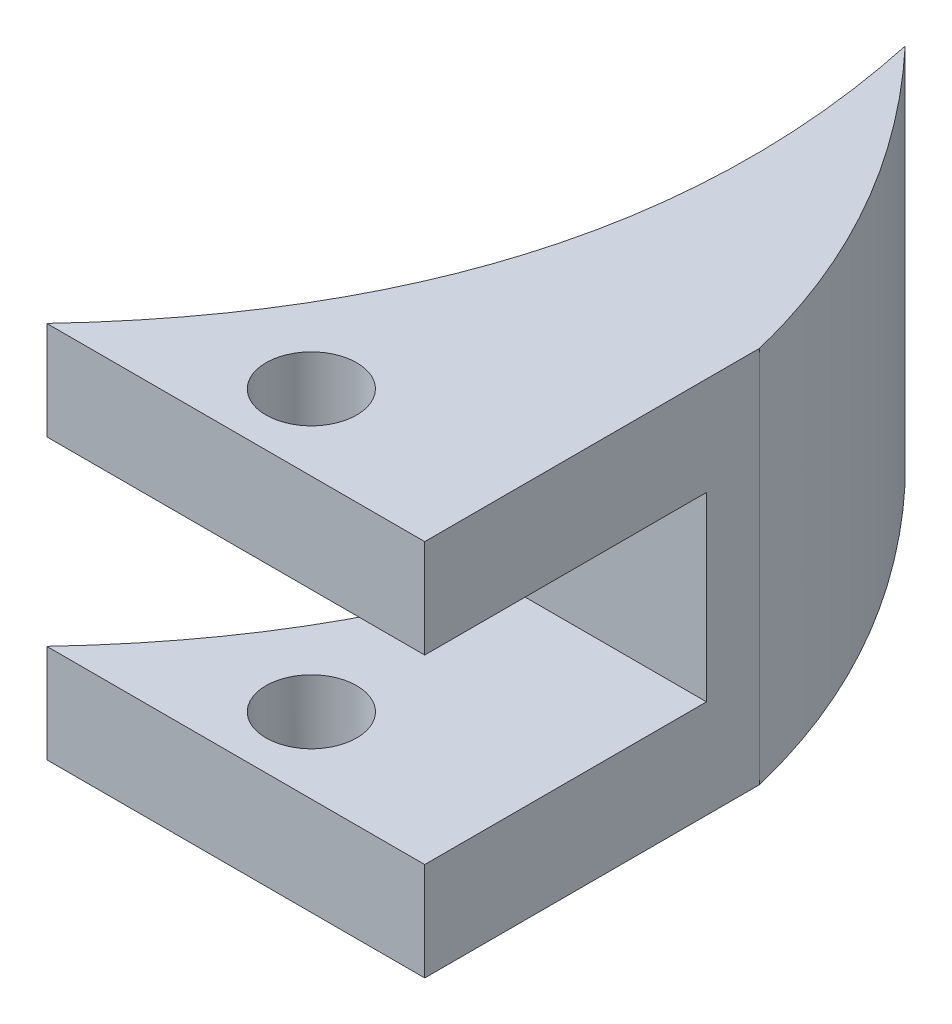
SolidWorks part; units mm, degrees
ref_plane "정면" through (0, 0, 0) normal (0, 0, 1) x (1, 0, 0)
ref_plane "윗면" through (0, 0, 0) normal (0, 1, 0) x (1, 0, 0)
ref_plane "우측면" through (0, 0, 0) normal (1, 0, 0) x (0, 0, -1)
sketch "스케치1" plane through (0, 0, 0) normal (0, 0, 1) x (1, 0, 0)
  line L1 (-12.5, -12.5) -> (12.5, -12.5)
  line L2 (-12.5, -12.5) -> (-12.5, 12.5)
  line L3 (-12.5, 12.5) -> (12.5, 12.5)
  line L4 (12.5, -12.5) -> (12.5, 12.5)
  line L5 (-12.5, -12.5) -> (12.5, 12.5) construction
  line L6 (-12.5, 12.5) -> (12.5, -12.5) construction
  point P0 (0, 0)
  dimension "D1" = 25
extrude "보스-돌출1" add sketch "스케치1" along normal blind 44.2842 contours L3 L4 L1 L2
sketch "스케치2" plane through (0, 12.5, 0) normal (0, 1, 0) x (1, 0, 0)
  line L0 (-12.5, -44.2842) -> (12.5, -44.2842) construction
  circle A0 centre (0, -39.2842) radius 3
  dimension "D1" = 6
  dimension "D2" = 5
extrude "컷-돌출1" cut sketch "스케치2" against normal blind 36.4068 contours A0
sketch "스케치4" plane through (0, 0, 44.2842) normal (0, 0, 1) x (1, 0, 0)
  line L0 (-12.5, -12.5) -> (-12.5, 12.5) construction
  line L1 (12.5, -6) -> (-12.5, -6)
  line L2 (12.5, -6) -> (12.5, 6)
  line L3 (12.5, 6) -> (-12.5, 6)
  line L4 (-12.5, -6) -> (-12.5, 6)
  line L5 (12.5, -6) -> (-12.5, 6) construction
  line L6 (12.5, 6) -> (-12.5, -6) construction
  point P0 (0, 0)
  dimension "D1" = 12
extrude "컷-돌출2" cut sketch "스케치4" against normal blind 18.6398
sketch "스케치5" plane through (0, 12.5, 0) normal (0, 1, 0) x (1, 0, 0)
  line L2 (-12.5, 0) -> (12.5, 0) construction
  line L3 (12.5, -44.2842) -> (12.5, 0) construction
  line L5 (-47.0249, -52.2283) -> (5.7054, 41.4619)
  line L6 (5.7054, 41.4619) -> (28.8317, -24.1558)
  line L7 (28.8317, -24.1558) -> (12.5, -44.2842)
  line L10 (-12.5, -44.2842) -> (-47.0249, -52.2283)
  spline S0 degree 2 poles (0, 0) (17.9426, -19.0695) (12.5, -44.2842) knots 0 0 0 1 1 1
  spline S1 degree 2 poles (0, 0) (5.4426, -25.2146) (-12.5, -44.2842) knots 0 0 0 1 1 1
extrude "컷-돌출3" cut sketch "스케치5" against normal blind 40
